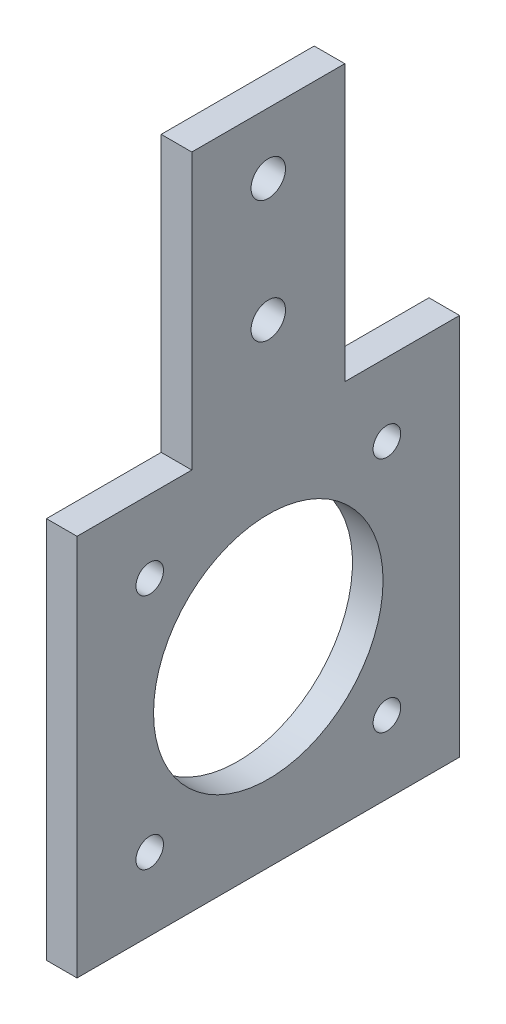
SolidWorks part; units mm, degrees
ref_plane "Front Plane" through (0, 0, 0) normal (0, 0, 1) x (1, 0, 0)
ref_plane "Top Plane" through (0, 0, 0) normal (0, 1, 0) x (1, 0, 0)
ref_plane "Right Plane" through (0, 0, 0) normal (1, 0, 0) x (0, 0, -1)
sketch "Sketch1" plane through (0, 0, 0) normal (0, 1, 0) x (1, 0, 0)
  line L1 (-10, -10) -> (10, -10)
  line L2 (-10, -10) -> (-10, 10)
  line L3 (-10, 10) -> (10, 10)
  line L4 (10, -10) -> (10, 10)
  line L5 (-10, -10) -> (10, 10) construction
  line L6 (-10, 10) -> (10, -10) construction
  line L7 (-14, 14) -> (14, 14)
  line L8 (-14, 14) -> (-14, -14)
  line L9 (-14, -14) -> (14, -14)
  line L10 (14, 14) -> (14, -14)
  line L11 (-14, 14) -> (14, -14) construction
  line L12 (-14, -14) -> (14, 14) construction
  point P0 (0, 0)
  point P5 (0, 0)
  dimension "D1" = 20
  dimension "D2" = 28
extrude "Boss-Extrude1" add sketch "Sketch1" along normal blind 40
sketch "Sketch2" plane through (-14, 0, 0) normal (-1, 0, 0) x (0, 0, 1)
  line L0 (0, 40) -> (0, 32)
  line L1 (0, 0) -> (0, 16)
  line L4 (-14, 0) -> (14, 0)
  line L5 (14, 0) -> (14, 40)
  line L6 (14, 40) -> (-14, 40)
  line L7 (-14, 40) -> (-14, 0)
  line L8 (-14, 0) -> (14, 0)
  line L9 (14, 0) -> (14, 40)
  line L10 (14, 40) -> (-14, 40)
  line L11 (-14, 40) -> (-14, 0)
  circle A0 centre (0, 32) radius 2.25
  circle A1 centre (0, 16) radius 2.25
  dimension "D3" = 4.5
  dimension "D5" = 4.5
  dimension "D2" = 8
  dimension "D4" = 16
  dimension "D1" = 0
extrude "Cut-Extrude1" cut sketch "Sketch2" against normal blind 30
sketch "Sketch5" plane through (-14, 0, 0) normal (-1, 0, 0) x (0, 0, 1)
  line L0 (0, 0) -> (0, -21)
  line L1 (0, -21) -> (-15.4998, -5.5002) construction
  line L2 (-25, -46) -> (25, -46)
  line L3 (-25, -46) -> (-25, 4)
  line L4 (-14, 0) -> (14, 0)
  line L5 (14, 0) -> (14, 40)
  line L6 (14, 40) -> (-14, 40)
  line L7 (-14, 40) -> (-14, 0)
  line L8 (-14, 0) -> (14, 0)
  line L9 (14, 0) -> (14, 40)
  line L10 (14, 40) -> (-14, 40)
  line L11 (-14, 40) -> (-14, 0)
  line L12 (-25, 4) -> (25, 4)
  line L13 (25, -46) -> (25, 4)
  line L14 (-25, -46) -> (25, 4) construction
  line L15 (-25, 4) -> (25, -46) construction
  line L16 (-15.4998, -5.5002) -> (15.4998, -5.5002) construction
  line L17 (15.4998, -5.5002) -> (15.4998, -36.4998) construction
  line L18 (15.4998, -36.4998) -> (-15.4998, -36.4998) construction
  circle A0 centre (-15.4998, -5.5002) radius 1.8
  circle A1 centre (15.4998, -5.5002) radius 1.8
  circle A2 centre (15.4998, -36.4998) radius 1.8
  circle A3 centre (-15.4998, -36.4998) radius 1.8
  circle A4 centre (0, -21) radius 15
  dimension "D5" = 3.6
  dimension "D6" = 30
  dimension "D2" = 21
  dimension "D3" = 50
  dimension "D4" = 21.92
  dimension "D1" = 0
extrude "Boss-Extrude2" add sketch "Sketch5" against normal up to surface (4 mm away) up to face at (-10, 16, -2.25)
sketch "Sketch6" plane through (0, 0, 0) normal (0, -1, 0) x (1, 0, 0)
  line L0 (-10, 14) -> (14, 14) construction
  line L1 (-10, 14) -> (14, 14)
  line L2 (-10, 14) -> (-10, -14)
  line L3 (-10, -14) -> (14, -14)
  line L4 (14, 14) -> (14, -14)
  dimension "D1" = 24
extrude "Cut-Extrude2" cut sketch "Sketch6" against normal blind 40
sketch "Sketch7" plane through (-14, 0, 0) normal (-1, 0, 0) x (0, 0, 1)
  line L0 (-10, 0) -> (10, 0)
  line L1 (-10, 0) -> (-10, 40)
  line L2 (-14, 40) -> (14, 40) construction
  line L3 (-10, 40) -> (10, 40)
  line L4 (10, 40) -> (10, 0)
  line L6 (-14, 40) -> (-10, 40)
  line L7 (-14, 40) -> (-14, 4)
  line L8 (-14, 4) -> (-10, 4)
  line L9 (-10, 40) -> (-10, 4)
  line L10 (14, 40) -> (10, 40)
  line L11 (14, 40) -> (14, 4)
  line L12 (14, 4) -> (10, 4)
  line L13 (10, 40) -> (10, 4)
  point P4 (0, 0)
  line M7 (-14, 40) -> (-14, 4)
  line M13 (14, 4) -> (14, 40)
  line M14 (14, 40) -> (-14, 40)
  dimension "D1" = 20
  dimension "D2" = 36
  dimension "D3" = 4
  dimension "D4" = 36
  dimension "D5" = 4
extrude "Cut-Extrude3" cut sketch "Sketch7" against normal blind 4 contours L8 L1 M7 M14 | L12 L4 M13 M14
